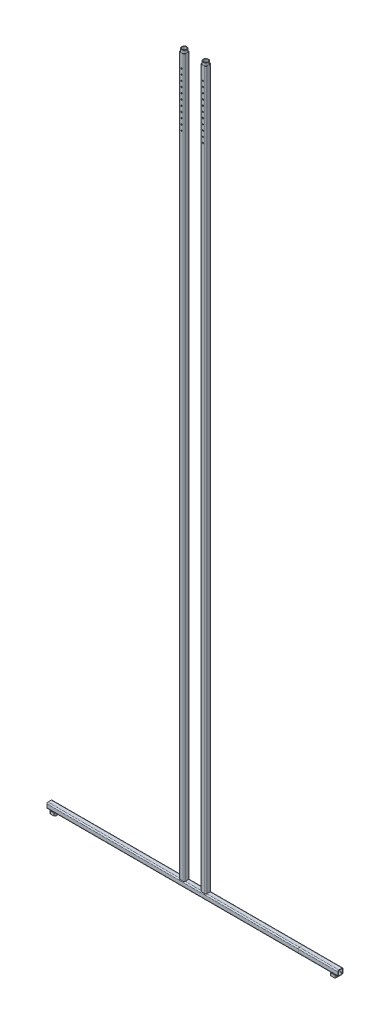
SolidWorks part; units mm, degrees
material "ASTM A36 Steel"
ref_plane "Front Plane" through (0, 0, 0) normal (0, 0, 1) x (1, 0, 0)
ref_plane "Top Plane" through (0, 0, 0) normal (0, 1, 0) x (1, 0, 0)
ref_plane "Right Plane" through (0, 0, 0) normal (1, 0, 0) x (0, 0, -1)
sketch "Sketch2" plane through (0, 0, 0) normal (0, 0, 1) x (1, 0, 0)
  line L0 (385.4461, 689.476) -> (385.4461, -1970.524)
  line L1 (305.4461, 689.476) -> (305.4461, -1970.524)
  line L2 (-174.5539, -1990.524) -> (-174.5539, -2000.524)
  line L3 (865.4461, -1990.524) -> (865.4461, -2000.524)
  line L4 (739.4461, -1980.524) -> (-194.5539, -1980.524)
  line L5 (739.4461, -1980.524) -> (885.4461, -1980.524)
  dimension "D1" = 2660
  dimension "D2" = 80
  dimension "D3" = 500
  dimension "D4" = 20
  dimension "D5" = 20
  dimension "D6" = 500
other "Square tube 20 X 20 X 2(1)"
ref_plane "Plane2" through (385.4461, 689.476, 0) normal (0, -1, 0) x (1, 0, 0)
sketch "Sketch1" plane through (385.4461, 689.476, 0) normal (0, -1, 0) x (1, 0, 0)
  line L0 (-6, -8) -> (6, -8)
  line L1 (-8, -6) -> (-8, 6)
  line L2 (6, 8) -> (-6, 8)
  line L3 (8, 6) -> (8, -6)
  line L4 (-6, -10) -> (6, -10)
  line L5 (-10, -6) -> (-10, 6)
  line L6 (6, 10) -> (-6, 10)
  line L7 (10, 6) -> (10, -6)
  arc A0 (10, 6) -> (6, 10) centre (6, 6) ccw
  arc A1 (6, -10) -> (10, -6) centre (6, -6) ccw
  arc A2 (-10, -6) -> (-6, -10) centre (-6, -6) ccw
  arc A3 (-6, 10) -> (-10, 6) centre (-6, 6) ccw
  arc A4 (-6, 8) -> (-8, 6) centre (-6, 6) ccw
  arc A5 (8, 6) -> (6, 8) centre (6, 6) ccw
  arc A6 (6, -8) -> (8, -6) centre (6, -6) ccw
  arc A7 (-8, -6) -> (-6, -8) centre (-6, -6) ccw
  point P0 (-10, 0)
  point P1 (10, 0)
  point P2 (0, 10)
  point P3 (0, -10)
  point P4 (0, 0)
  point P5 (-10, -10)
  point P6 (10, -10)
  point P7 (10, 10)
  point P8 (-10, 10)
  point P33 (0, 0)
  dimension "D1" = 4
  dimension "Thickness" = 2
  dimension "V_leg" = 20
other "Square tube 20 X 20 X 2(2)"
ref_plane "Plane3" through (739.4461, -1980.524, 0) normal (-1, 0, 0) x (0, -1, 0)
sketch "Sketch11" plane through (739.4461, -1980.524, 0) normal (-1, 0, 0) x (0, -1, 0)
  line L0 (-6, -8) -> (6, -8)
  line L1 (-8, -6) -> (-8, 6)
  line L2 (6, 8) -> (-6, 8)
  line L3 (8, 6) -> (8, -6)
  line L4 (-6, -10) -> (6, -10)
  line L5 (-10, -6) -> (-10, 6)
  line L6 (6, 10) -> (-6, 10)
  line L7 (10, 6) -> (10, -6)
  arc A0 (10, 6) -> (6, 10) centre (6, 6) ccw
  arc A1 (6, -10) -> (10, -6) centre (6, -6) ccw
  arc A2 (-10, -6) -> (-6, -10) centre (-6, -6) ccw
  arc A3 (-6, 10) -> (-10, 6) centre (-6, 6) ccw
  arc A4 (-6, 8) -> (-8, 6) centre (-6, 6) ccw
  arc A5 (8, 6) -> (6, 8) centre (6, 6) ccw
  arc A6 (6, -8) -> (8, -6) centre (6, -6) ccw
  arc A7 (-8, -6) -> (-6, -8) centre (-6, -6) ccw
  point P0 (-10, 0)
  point P1 (10, 0)
  point P2 (0, 10)
  point P3 (0, -10)
  point P4 (0, 0)
  point P5 (-10, -10)
  point P6 (10, -10)
  point P7 (10, 10)
  point P8 (-10, 10)
  point P33 (0, 0)
  dimension "D1" = 4
  dimension "Thickness" = 2
  dimension "V_leg" = 20
other "Square tube 20 X 20 X 2(4)"
ref_plane "Plane5" through (-174.5539, -1990.524, 0) normal (0, -1, 0) x (1, 0, 0)
sketch "Sketch13" plane through (-174.5539, -1990.524, 0) normal (0, -1, 0) x (1, 0, 0)
  line L0 (-6, -8) -> (6, -8)
  line L1 (-8, -6) -> (-8, 6)
  line L2 (6, 8) -> (-6, 8)
  line L3 (8, 6) -> (8, -6)
  line L4 (-6, -10) -> (6, -10)
  line L5 (-10, -6) -> (-10, 6)
  line L6 (6, 10) -> (-6, 10)
  line L7 (10, 6) -> (10, -6)
  arc A0 (10, 6) -> (6, 10) centre (6, 6) ccw
  arc A1 (6, -10) -> (10, -6) centre (6, -6) ccw
  arc A2 (-10, -6) -> (-6, -10) centre (-6, -6) ccw
  arc A3 (-6, 10) -> (-10, 6) centre (-6, 6) ccw
  arc A4 (-6, 8) -> (-8, 6) centre (-6, 6) ccw
  arc A5 (8, 6) -> (6, 8) centre (6, 6) ccw
  arc A6 (6, -8) -> (8, -6) centre (6, -6) ccw
  arc A7 (-8, -6) -> (-6, -8) centre (-6, -6) ccw
  point P0 (-10, 0)
  point P1 (10, 0)
  point P2 (0, 10)
  point P3 (0, -10)
  point P4 (0, 0)
  point P5 (-10, -10)
  point P6 (10, -10)
  point P7 (10, 10)
  point P8 (-10, 10)
  point P33 (0, 0)
  dimension "D1" = 4
  dimension "Thickness" = 2
  dimension "V_leg" = 20
sketch "Sketch14" plane through (0, 0, -10) normal (0, 0, -1) x (-1, 0, 0)
  line L0 (-379.4461, 689.476) -> (-391.4461, 689.476) construction
  circle A0 centre (-384.8471, 639.476) radius 2.5
  dimension "D1" = 50
extrude "Cut-Extrude1" cut sketch "Sketch14" against normal through all both and the other way through all
pattern_linear "LPattern1" count 11 spacing 20 along (0, -1, 0) of "Cut-Extrude1"
sketch "Sketch15" plane through (0, 0, -10) normal (0, 0, -1) x (-1, 0, 0)
  line L0 (-299.4461, 689.476) -> (-311.4461, 689.476) construction
  circle A0 centre (-305.4461, 639.476) radius 2.5
  dimension "D1" = 50
extrude "Cut-Extrude2" cut sketch "Sketch15" against normal through all both and the other way through all
pattern_linear "LPattern2" count 11 spacing 20 along (0, -1, 0) of "Cut-Extrude2"
sketch "Sketch16" plane through (0, 689.476, 0) normal (0, 1, 0) x (1, 0, 0)
  circle A0 centre (385.4461, 0) radius 10
  circle A1 centre (385.4461, 0) radius 8
extrude "Boss-Extrude1" add sketch "Sketch16" along normal blind 10 separate body
sketch "Sketch18" plane through (0, 689.476, 0) normal (0, 1, 0) x (1, 0, 0)
  circle A0 centre (305.3878, 0.0158) radius 8.0158
  circle A1 centre (305.3878, 0.0158) radius 9.9419
extrude "Boss-Extrude2" add sketch "Sketch18" along normal blind 10 separate body
